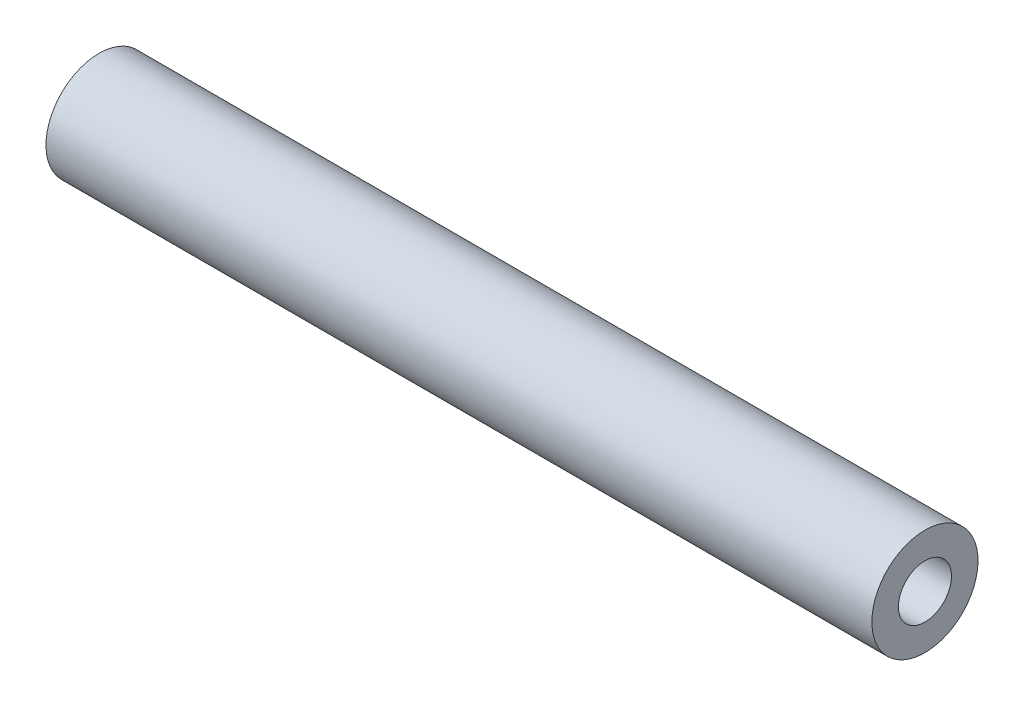
SolidWorks part; units mm, degrees
material "Cast Carbon Steel"
ref_plane "Front Plane" through (0, 0, 0) normal (0, 0, 1) x (1, 0, 0)
ref_plane "Top Plane" through (0, 0, 0) normal (0, 1, 0) x (1, 0, 0)
ref_plane "Right Plane" through (0, 0, 0) normal (1, 0, 0) x (0, 0, -1)
sketch "Sketch1" plane through (0, 0, 0) normal (0, 0, 1) x (1, 0, 0)
  line L0 (0, 3.175) -> (0, 6.35)
  line L1 (0, -64.5222) -> (0, 64.5222) construction
  line L3 (98.806, 6.35) -> (98.806, 3.175)
  line L5 (86.106, 0) -> (12.7, 0)
  line L11 (0, 6.35) -> (98.806, 6.35)
  line L15 (0, 3.175) -> (12.7, 3.175)
  line L16 (12.7, 0) -> (12.7, 3.175)
  line L20 (98.806, 3.175) -> (86.106, 3.175)
  line L21 (86.106, 0) -> (86.106, 3.175)
  dimension "D2" = 98.806
revolve "Revolve1" add sketch "Sketch1" angle 360 about L5
